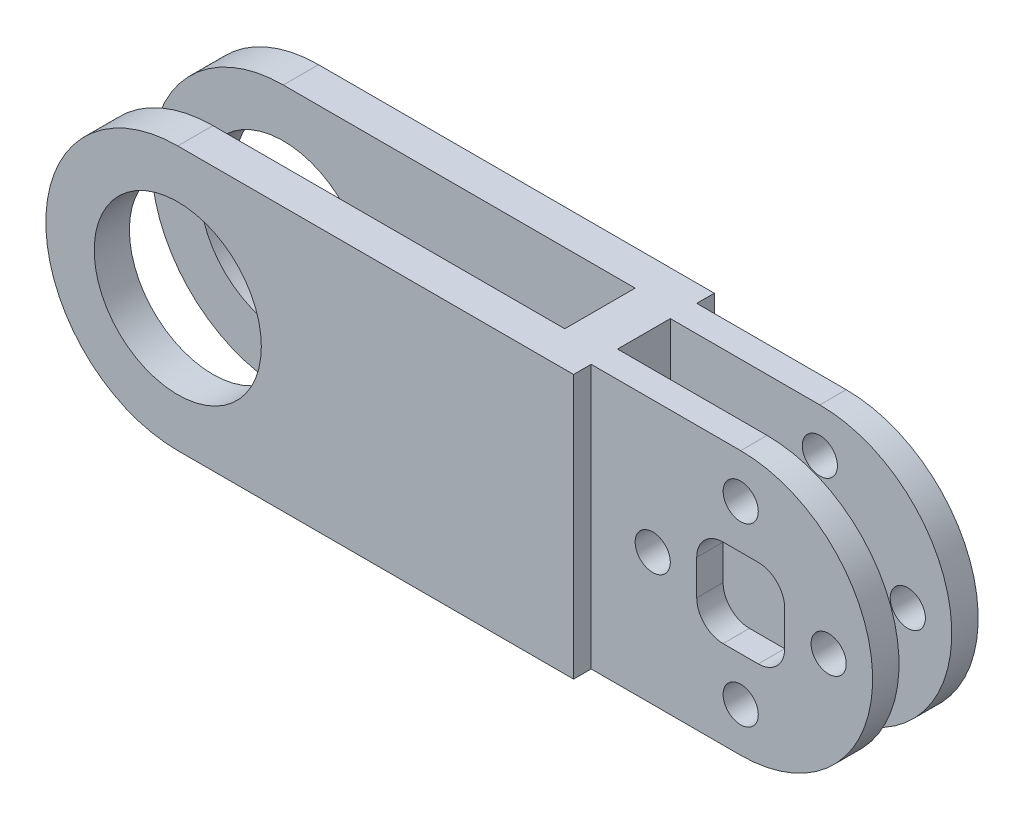
SolidWorks part; units mm, degrees
ref_plane "前视基准面" through (0, 0, 0) normal (0, 0, 1) x (1, 0, 0)
ref_plane "上视基准面" through (0, 0, 0) normal (0, 1, 0) x (1, 0, 0)
ref_plane "右视基准面" through (0, 0, 0) normal (1, 0, 0) x (0, 0, -1)
sketch "草图1" plane through (0, 0, 0) normal (0, 0, 1) x (1, 0, 0)
  line L0 (0, 0) -> (62, 0) construction
  line L1 (0, 15) -> (62, 15)
  line L2 (0, -15) -> (62, -15)
  arc A0 (0, 15) -> (0, -15) centre (0, 0) ccw
  arc A1 (62, -15) -> (62, 15) centre (62, 0) ccw
  point P3 (31, 0)
  dimension "D2" = 30
  dimension "D1" = 62
extrude "凸台-拉伸1" add sketch "草图1" along normal blind 16
sketch "草图2" plane through (0, 0, 16) normal (0, 0, 1) x (1, 0, 0)
  line L1 (57, -5) -> (67, -5)
  line L2 (57, -5) -> (57, 5)
  line L3 (57, 5) -> (67, 5)
  line L4 (67, -5) -> (67, 5)
  line L5 (57, -5) -> (67, 5) construction
  line L6 (57, 5) -> (67, -5) construction
  circle A0 centre (0, 0) radius 9.5
  circle A1 centre (62, 0) radius 10 construction
  circle A2 centre (62, 10) radius 2
  circle A3 centre (72, 0) radius 2
  circle A4 centre (62, -10) radius 2
  circle A5 centre (52, 0) radius 2
  dimension "D1" = 19
  dimension "D2" = 20
  dimension "D3" = 4
  dimension "D5" = 10
  dimension "D6" = 10
  dimension "D4" = 4
extrude "切除-拉伸1" cut sketch "草图2" against normal blind 16
fillet "圆角1" radius 3 4 edges at (57, -5, 8) (57, 5, 8) (67, 5, 8) (67, -5, 8)
sketch "草图4" plane through (0, 0, 0) normal (0, 1, 0) x (1, 0, 0)
  line L0 (-1000, -8) -> (49000, -8) construction
  line L1 (0, -16) -> (0, 0) construction
  line L2 (-15, 0) -> (-15, -16) construction
  line L3 (40, -12) -> (-15, -12)
  line L4 (40, -12) -> (40, -4)
  line L5 (40, -4) -> (-15, -4)
  line L6 (-15, -12) -> (-15, -4)
  line L7 (40, -12) -> (-15, -4) construction
  line L8 (40, -4) -> (-15, -12) construction
  point P1 (12.5, -8)
  point P5 (0, -8)
  dimension "D1" = 55
  dimension "D2" = 8
extrude "切除-拉伸5" cut sketch "草图4" against normal blind 15 and the other way blind 15
sketch "草图5" plane through (0, 0, 0) normal (0, 1, 0) x (1, 0, 0)
  line L0 (40, -8) -> (45, -8) construction
  line L1 (40, -12) -> (40, -4) construction
  line L2 (45, -8) -> (45, -11)
  line L3 (45, -11) -> (77, -11)
  line L4 (77, -16) -> (77, 0) construction
  line L5 (77, -11) -> (77, -5)
  line L6 (77, -5) -> (45, -5)
  line L7 (45, -5) -> (45, -8)
  line L8 (62, 0) -> (0, 0) construction
  line L9 (45, 0) -> (77, 0)
  line L10 (45, 0) -> (45, -2)
  line L11 (45, -2) -> (77, -2)
  line L12 (77, 0) -> (77, -2)
  line L13 (62, -16) -> (0, -16) construction
  line L14 (45, -16) -> (77, -16)
  line L15 (45, -16) -> (45, -14)
  line L16 (45, -14) -> (77, -14)
  line L17 (77, -16) -> (77, -14)
  dimension "D1" = 5
  dimension "D2" = 6
  dimension "D3" = 3
  dimension "D4" = 2
  dimension "D5" = 32
  dimension "D6" = 2
  dimension "D7" = 32
extrude "切除-拉伸6" cut sketch "草图5" against normal blind 15 and the other way blind 15
